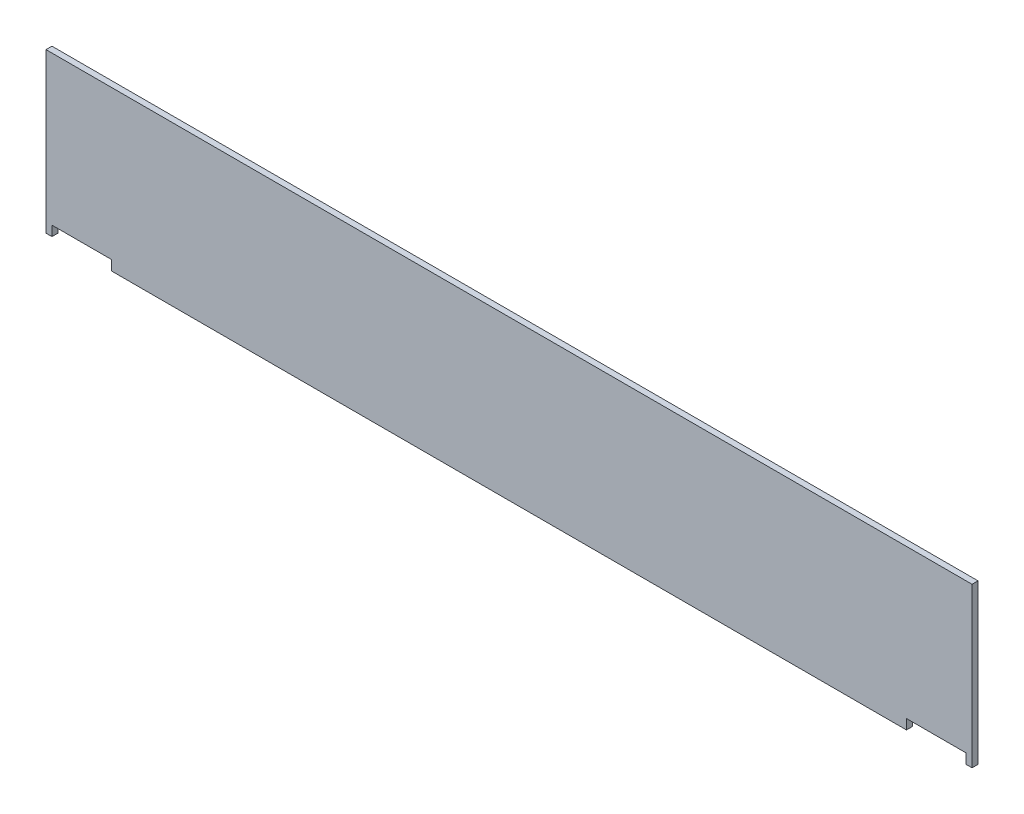
SolidWorks part; units mm, degrees
ref_plane "Přední rovina" through (0, 0, 0) normal (0, 0, 1) x (1, 0, 0)
ref_plane "Horní rovina" through (0, 0, 0) normal (0, 1, 0) x (1, 0, 0)
ref_plane "Pravá rovina" through (0, 0, 0) normal (1, 0, 0) x (0, 0, -1)
sketch "Skica1" plane through (0, 0, 0) normal (0, 0, 1) x (1, 0, 0)
  line L0 (-226.6525, 0) -> (-226.6525, 80)
  line L1 (-226.6525, 80) -> (239.3475, 80)
  line L2 (239.3475, 80) -> (239.3475, 0)
  line L3 (239.3475, 0) -> (236.3475, 0)
  line L4 (236.3475, 0) -> (236.3475, 5)
  line L5 (236.3475, 5) -> (206.3475, 5)
  line L6 (206.3475, 5) -> (206.3475, 0)
  line L7 (206.3475, 0) -> (-193.6525, 0)
  line L8 (-193.6525, 0) -> (-193.6525, 5)
  line L9 (-193.6525, 5) -> (-223.6525, 5)
  line L10 (-223.6525, 5) -> (-223.6525, 0)
  line L11 (-223.6525, 0) -> (-226.6525, 0)
  dimension "D1" = 466
  dimension "D2" = 80
  dimension "D3" = 5
  dimension "D4" = 30
  dimension "D5" = 3
extrude "Přidat vysunutím1" add sketch "Skica1" along normal blind 3
